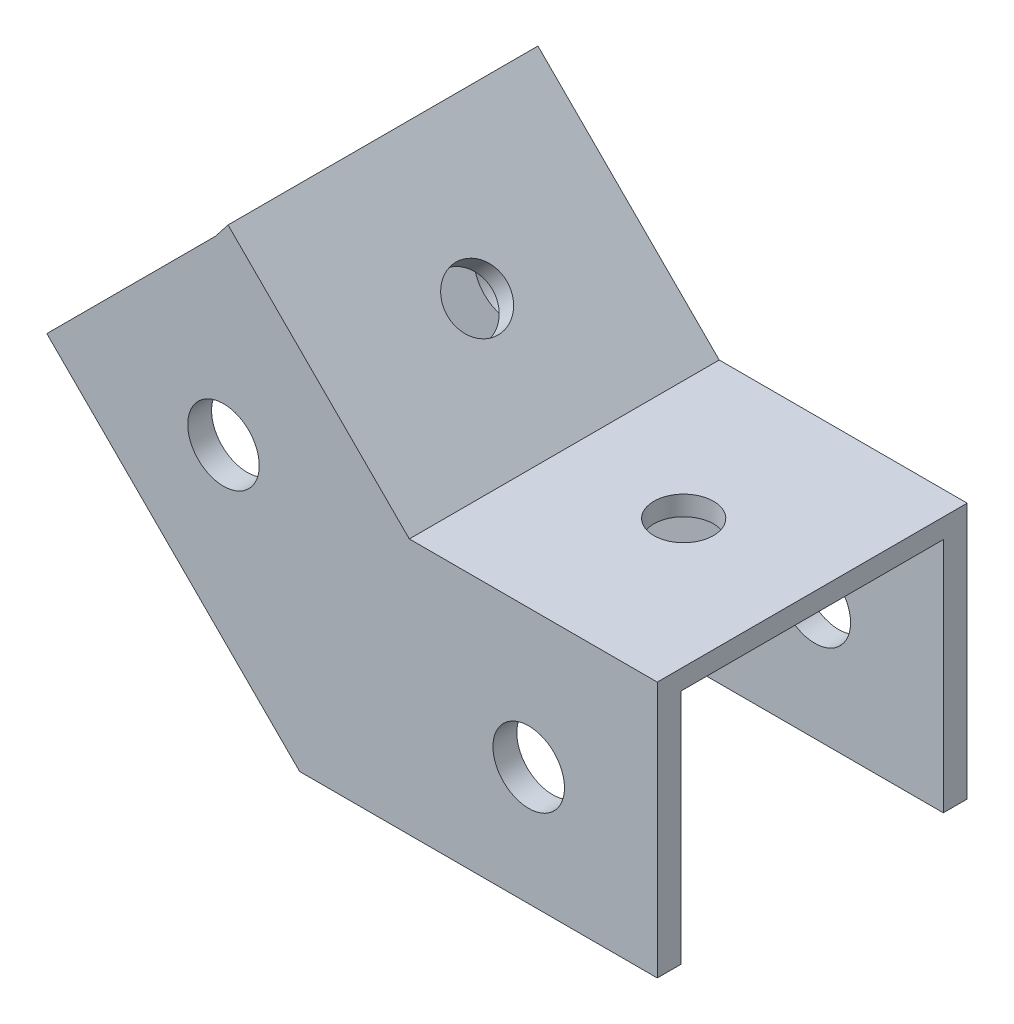
SolidWorks part; units mm, degrees
ref_plane "Plano frontal" through (0, 0, 0) normal (0, 0, 1) x (1, 0, 0)
ref_plane "Plano superior" through (0, 0, 0) normal (0, 1, 0) x (1, 0, 0)
ref_plane "Plano direito" through (0, 0, 0) normal (1, 0, 0) x (0, 0, -1)
sketch "Esboço1" plane through (0, 0, 0) normal (0, 0, 1) x (1, 0, 0)
  line L37 (-42.3663, -154.1466) -> (-42.3663, -174)
  line L44 (-42.3663, -174) -> (-72.3663, -174)
  line L46 (-42.3663, -154.1466) -> (-63.9354, -154.1466)
  line L47 (-72.3663, -174) -> (-93.5795, -152.7868)
  line L49 (-93.5795, -152.7868) -> (-79.4373, -138.6447)
  line L50 (-79.4373, -138.6447) -> (-63.9354, -154.1466)
  line L55 (-78.0776, -168.2887) -> (-93.5795, -152.7868)
  line L56 (-78.0776, -168.2887) -> (-93.5795, -152.7868)
  line L57 (-93.5795, -152.7868) -> (-85.8285, -160.5377)
  circle A4 centre (-78.7575, -153.4667) radius 3
  circle A6 centre (-53.1509, -164.0733) radius 3
  point P0 (0, 0)
  point P6 (-53.1509, -164.0733)
extrude "Ressalto-extrusão1" add sketch "Esboço1" along normal blind 2 contours L50 L49 L56 L47 L44 L37 L46 A6 A4
sketch "Esboço5" plane through (0, 0, 2) normal (0, 0, 1) x (1, 0, 0)
  line L0 (-79.4373, -138.6447) -> (-78.3767, -137.2909)
  line L1 (-63.1676, -152.5) -> (-42.3663, -152.5)
  line L3 (-42.3663, -154.1466) -> (-42.3663, -152.5)
  line L4 (-63.1676, -152.5) -> (-78.3767, -137.2909)
  line L6 (-63.9354, -154.1466) -> (-63.1676, -152.5)
  point P3 (-63.9354, -154.1466)
  point P5 (0, 0)
  point P9 (-79.4373, -138.6447)
  point P10 (-63.9354, -154.1466)
  point P11 (0, 0)
  point P12 (-42.3663, -154.1466)
extrude "Ressalto-extrusão2" add sketch "Esboço5" against normal blind 13
mirror "Espelhar2" about plane through (0, 0, -11) normal (0, 0, 1) of "Ressalto-extrusão1", "Ressalto-extrusão2"
sketch "Esboço6" plane through (-109.041, -109.041, 0) normal (-0.7071, -0.7071, 0) x (-0.7071, 0.7071, 0)
  circle A0 centre (-52.8274, 11) radius 2.5
  point P6 (-52.8274, 11)
sketch "Esboço7" plane through (0, -154.1466, 0) normal (0, -1, 0) x (1, 0, 0)
  circle A0 centre (-53.1509, -11) radius 2.5
  point P14 (-53.1509, -11)
extrude "Corte-extrusão1" cut sketch "Esboço7" against normal up to next
extrude "Corte-extrusão2" cut sketch "Esboço6" against normal up to next
